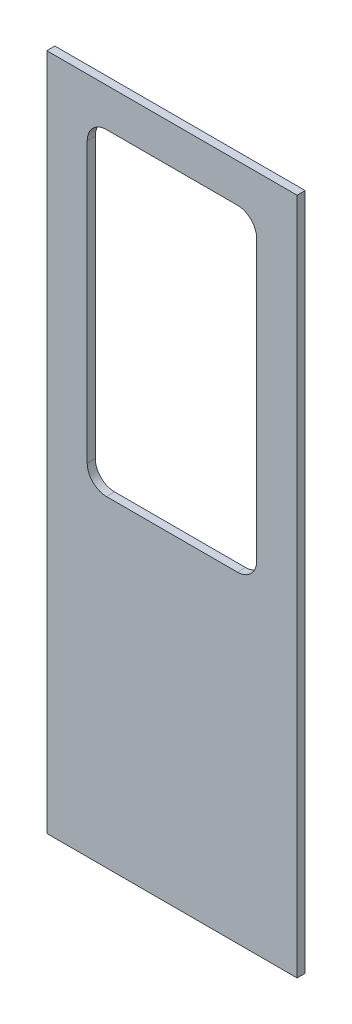
SolidWorks part; units mm, degrees
ref_plane "Front Plane" through (0, 0, 0) normal (0, 0, 1) x (1, 0, 0)
ref_plane "Top Plane" through (0, 0, 0) normal (0, 1, 0) x (1, 0, 0)
ref_plane "Right Plane" through (0, 0, 0) normal (1, 0, 0) x (0, 0, -1)
sketch "Sketch1" plane through (0, 0, 0) normal (0, 0, 1) x (1, 0, 0)
  line L0 (0, 111.76) -> (0, -111.76) construction
  line L1 (41.275, -111.76) -> (-41.275, -111.76)
  line L2 (41.275, -111.76) -> (41.275, 111.76)
  line L3 (41.275, 111.76) -> (-41.275, 111.76)
  line L4 (-41.275, -111.76) -> (-41.275, 111.76)
  line L5 (41.275, -111.76) -> (-41.275, 111.76) construction
  line L6 (41.275, 111.76) -> (-41.275, -111.76) construction
  line L7 (-21.59, 99.06) -> (21.59, 99.06)
  line L8 (-27.94, 92.71) -> (-27.94, 0.635)
  line L9 (-21.59, -5.715) -> (21.59, -5.715)
  line L10 (27.94, 92.71) -> (27.94, 0.635)
  arc A2 (27.94, 92.71) -> (21.59, 99.06) centre (21.59, 92.71) ccw
  arc A3 (21.59, -5.715) -> (27.94, 0.635) centre (21.59, 0.635) ccw
  arc A4 (-27.94, 0.635) -> (-21.59, -5.715) centre (-21.59, 0.635) ccw
  arc A5 (-21.59, 99.06) -> (-27.94, 92.71) centre (-21.59, 92.71) ccw
  point P0 (0, 0)
  point P18 (0, 99.06)
  point P21 (27.94, 99.06)
  point P28 (-27.94, 99.06)
  dimension "D7" = 6.35
  dimension "D1" = 82.55
  dimension "D2" = 223.52
  dimension "D4" = 55.88
  dimension "D5" = 104.775
  dimension "D6" = 106.045
extrude "Boss-Extrude1" add sketch "Sketch1" along normal blind 2.667
